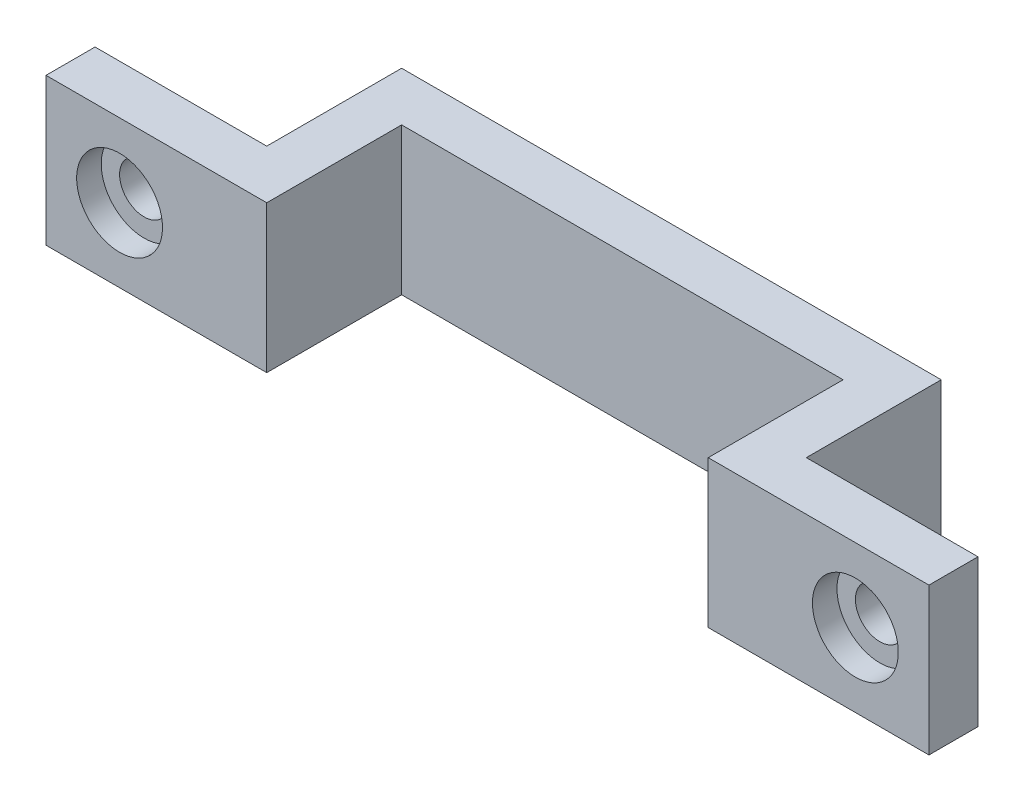
SolidWorks part; units mm, degrees
ref_plane "Přední rovina" through (0, 0, 0) normal (0, 0, 1) x (1, 0, 0)
ref_plane "Horní rovina" through (0, 0, 0) normal (0, 1, 0) x (1, 0, 0)
ref_plane "Pravá rovina" through (0, 0, 0) normal (1, 0, 0) x (0, 0, -1)
sketch "Skica1" plane through (0, 0, 0) normal (0, 0, 1) x (1, 0, 0)
  line L0 (0, 0) -> (0, 6) construction
  line L1 (0, 0) -> (36, 0) construction
  line L2 (-36, 6) -> (36, 6)
  line L3 (36, 6) -> (36, -6)
  line L4 (-36, -6) -> (36, -6)
  line L5 (-36, 6) -> (-36, -6)
  line L6 (0, 0) -> (-30, 0) construction
  circle A0 centre (-30, 0) radius 2
  circle A1 centre (30, 0) radius 2
  point P10 (0, -6)
  dimension "D4" = 4
  dimension "D1" = 36
  dimension "D2" = 72
  dimension "D3" = 12
  dimension "D5" = 30
extrude "Přidat vysunutím1" add sketch "Skica1" along normal blind 4
sketch "Skica2" plane through (0, 0, 4) normal (0, 0, 1) x (1, 0, 0)
  line L0 (-30, 0) -> (-30, 6) construction
  line L1 (36, 6) -> (-36, 6) construction
  line L2 (0, 0) -> (0, 6) construction
  circle A0 centre (-30, 0) radius 3.5
  circle A1 centre (30, 0) radius 3.5
  dimension "D1" = 7
extrude "Odebrat vysunutím1" cut sketch "Skica2" against normal blind 2
sketch "Skica3" plane through (0, 0, 0) normal (0, 0, -1) x (-1, 0, 0)
  line L0 (0, 0) -> (0, 6) construction
  line L1 (-36, 6) -> (36, 6) construction
  line L2 (0, 0) -> (22, 0) construction
  line L3 (-22, 6) -> (22, 6)
  line L4 (22, 6) -> (22, -6)
  line L5 (-22, 6) -> (-22, -6)
  line L6 (-22, -6) -> (22, -6)
  point P11 (-22, 0)
  dimension "D1" = 44
extrude "Přidat vysunutím2" add sketch "Skica3" along normal blind 11
sketch "Skica4" plane through (0, 0, 4) normal (0, 0, 1) x (1, 0, 0)
  line L0 (0, 0) -> (0, 6) construction
  line L1 (36, 6) -> (-36, 6) construction
  line L2 (0, 0) -> (18, 0) construction
  line L3 (18, -6) -> (18, 6)
  line L4 (18, 6) -> (-18, 6)
  line L5 (-18, -6) -> (-18, 6)
  line L6 (18, -6) -> (-18, -6)
  point P11 (-18, 0)
  dimension "D1" = 36
extrude "Odebrat vysunutím2" cut sketch "Skica4" against normal blind 11
